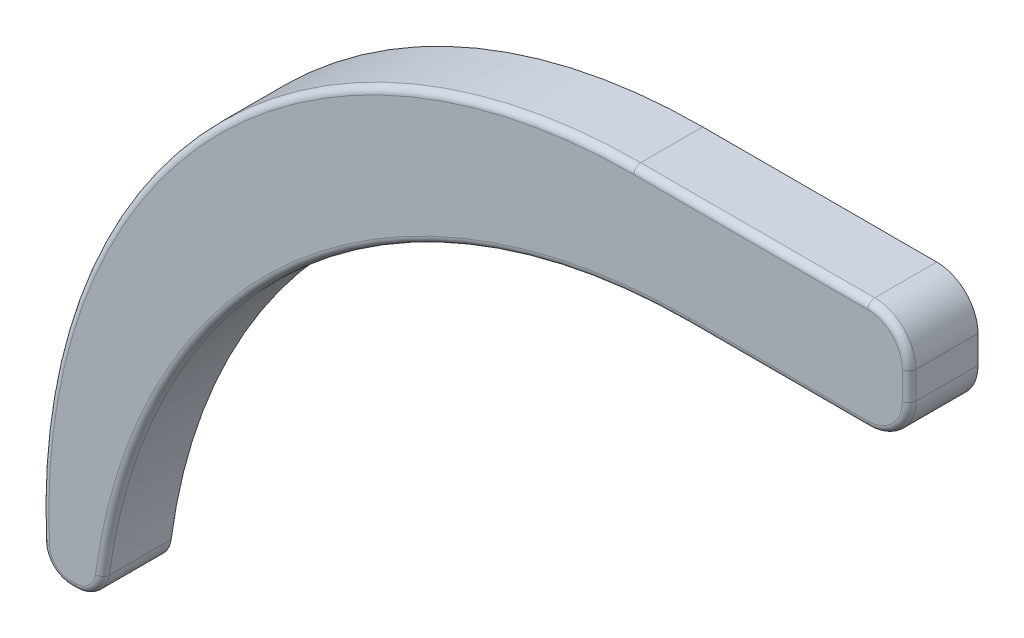
SolidWorks part; units mm, degrees
ref_plane "Спереди" through (0, 0, 0) normal (0, 0, 1) x (1, 0, 0)
ref_plane "Сверху" through (0, 0, 0) normal (0, 1, 0) x (1, 0, 0)
ref_plane "Справа" through (0, 0, 0) normal (1, 0, 0) x (0, 0, -1)
sketch "Эскиз1" plane through (0, 0, 0) normal (0, 0, 1) x (1, 0, 0)
  line B0 (0.353, 0) -> (0, 0)
  line B1 (40.9512, 47) -> (57.9512, 47)
  line B2 (57.9512, 39) -> (44.9512, 39)
  line B3 (60.9512, 44) -> (60.9512, 42)
  arc B4 (-1.9976, 1.9024) -> (0, 0) centre (0, 2) ccw
  arc B5 (0.353, 0) -> (2.3351, 1.7333) centre (0.353, 2) ccw
  arc B6 (44.9512, 39) -> (2.3351, 1.7333) centre (44.9512, -4) ccw
  arc B7 (40.9512, 47) -> (-1.9976, 1.9024) centre (40.9512, 4) ccw
  arc B8 (57.9512, 39) -> (60.9512, 42) centre (57.9512, 42) ccw
  arc B9 (60.9512, 44) -> (57.9512, 47) centre (57.9512, 44) ccw
sketch_block_instance "Блок1-1"
sketch_block "Блок1"
extrude "Бобышка-Вытянуть1" add sketch "Эскиз1" along normal blind 5
fillet "Скругление1" radius 0.5 10 edges at (0.1765, 0, 5) (-1.3793, 0.5517, 5) (9.8128, 33.6547, 5) (49.4512, 47, 5) (60.0725, 46.1213, 5) (60.9512, 43, 5) (60.0725, 39.8787, 5) (51.4512, 39, 5) (16.6451, 28.3692, 5) (1.6695, 0.4945, 5)
